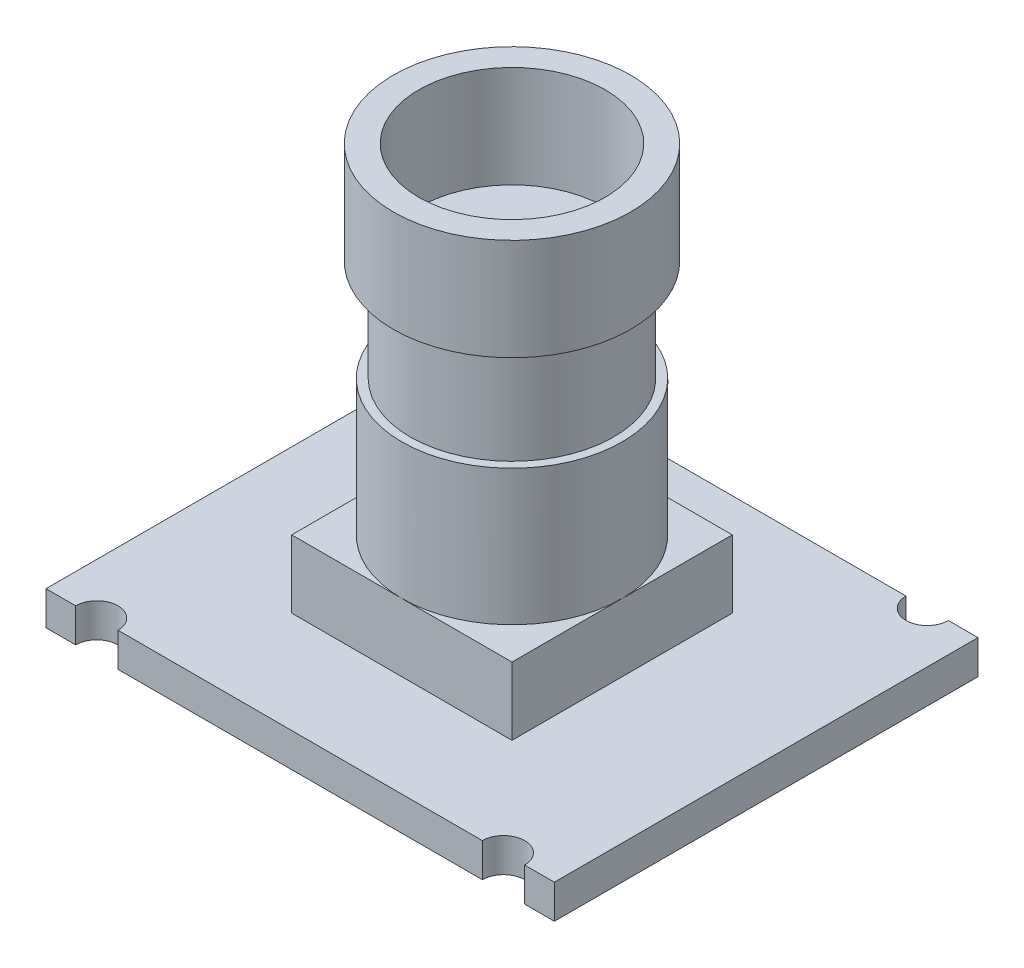
SolidWorks part; units mm, degrees
ref_plane "前基準面" through (0, 0, 0) normal (0, 0, 1) x (1, 0, 0)
ref_plane "上基準面" through (0, 0, 0) normal (0, 1, 0) x (1, 0, 0)
ref_plane "右基準面" through (0, 0, 0) normal (1, 0, 0) x (0, 0, -1)
sketch "草圖1" plane through (0, 0, 0) normal (0, 1, 0) x (1, 0, 0)
  line L1 (-15, -12.5) -> (15, -12.5)
  line L2 (-15, -12.5) -> (-15, 12.5)
  line L3 (-15, 12.5) -> (15, 12.5)
  line L4 (15, -12.5) -> (15, 12.5)
  line L5 (-15, -12.5) -> (15, 12.5) construction
  line L6 (-15, 12.5) -> (15, -12.5) construction
  point P0 (0, 0)
  dimension "D1" = 30
  dimension "D2" = 25
extrude "填料-伸長1" add sketch "草圖1" along normal blind 2
sketch "草圖2" plane through (0, 2, 0) normal (0, 1, 0) x (1, 0, 0)
  line L0 (15, 12.5) -> (-15, 12.5) construction
  line L1 (-15, -12.5) -> (15, -12.5) construction
  circle A0 centre (-12, 12.5) radius 1.25
  circle A1 centre (-12, -12.5) radius 1.25
  point P8 (0, 0)
  dimension "D2" = 2.5
  dimension "D1" = 12
extrude "除料-伸長1" cut sketch "草圖2" against normal through all
mirror "鏡射1" about plane through (0, 0, 0) normal (1, 0, 0) of "除料-伸長1"
sketch "草圖3" plane through (0, 2, 0) normal (0, 1, 0) x (1, 0, 0)
  line L1 (-6.5, -6.5) -> (6.5, -6.5)
  line L2 (-6.5, -6.5) -> (-6.5, 6.5)
  line L3 (-6.5, 6.5) -> (6.5, 6.5)
  line L4 (6.5, -6.5) -> (6.5, 6.5)
  line L5 (-6.5, -6.5) -> (6.5, 6.5) construction
  line L6 (-6.5, 6.5) -> (6.5, -6.5) construction
  point P0 (0, 0)
  dimension "D1" = 13
  dimension "D2" = 13
extrude "填料-伸長2" add sketch "草圖3" along normal blind 4
sketch "草圖4" plane through (0, 6, 0) normal (0, 1, 0) x (1, 0, 0)
  circle A0 centre (0, 0) radius 6.5
extrude "填料-伸長3" add sketch "草圖4" along normal blind 8
sketch "草圖5" plane through (0, 14, 0) normal (0, 1, 0) x (1, 0, 0)
  circle A0 centre (0, 0) radius 6
  dimension "D1" = 12
extrude "填料-伸長4" add sketch "草圖5" along normal blind 6
sketch "草圖6" plane through (0, 20, 0) normal (0, 1, 0) x (1, 0, 0)
  circle A0 centre (0, 0) radius 7
  circle A1 centre (0, 0) radius 5.5
  dimension "D1" = 14
  dimension "D2" = 11
extrude "填料-伸長5" add sketch "草圖6" along normal blind 6
